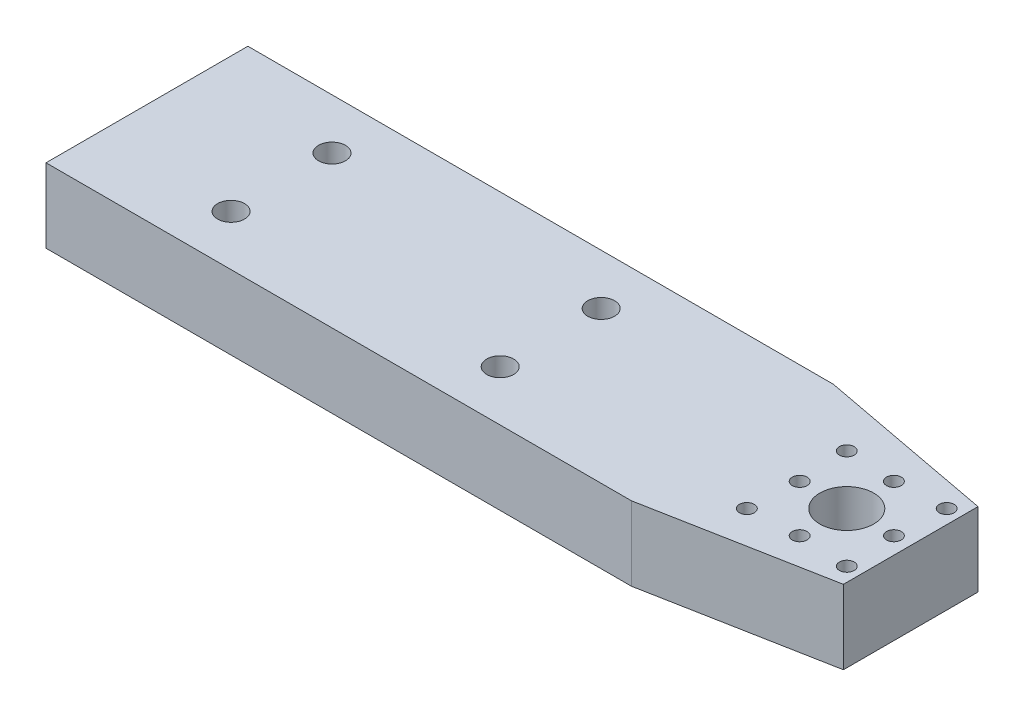
SolidWorks part; units mm, degrees
material "PF"
ref_plane "前视基准面" through (0, 0, 0) normal (0, 0, 1) x (1, 0, 0)
ref_plane "上视基准面" through (0, 0, 0) normal (0, 1, 0) x (1, 0, 0)
ref_plane "右视基准面" through (0, 0, 0) normal (1, 0, 0) x (0, 0, -1)
sketch "草图1" plane through (0, 0, 0) normal (0, 1, 0) x (1, 0, 0)
  line L1 (-41.2, 20) -> (78.8, 20)
  line L3 (-41.2, 0) -> (78.8, 0)
  line L4 (78.8, 20) -> (78.8, 0)
  arc A0 (-41.2, 20) -> (-41.2, 0) centre (-41.2, 10) ccw
  dimension "D1" = 20
  dimension "D2" = 120
extrude "凸台-拉伸1" add sketch "草图1" along normal blind 11
sketch "草图2" plane through (0, 11, 0) normal (0, 1, 0) x (1, 0, 0)
  line L0 (-41.2, 20) -> (-41.2, 0) construction
  line L1 (-41.2, 17) -> (-41.2, 3)
  circle A0 centre (-41.2, 3) radius 1.5
  circle A1 centre (-48.2, 10) radius 1.5
  circle A2 centre (-41.2, 17) radius 1.5
  circle A3 centre (-34.2, 10) radius 1.5
  circle A4 centre (-41.2, 10) radius 4
  point P7 (-41.2, 10)
  dimension "D1" = 4
extrude "切除-拉伸1" cut sketch "草图2" against normal blind 10 contours A1 | A2 L0 L1 | L0 A2 L1 | L1 L0 A0 | L0 L1 A0 | A4
sketch "草图4" plane through (0, 11, 0) normal (0, 1, 0) x (1, 0, 0)
  line L0 (78.8, 10) -> (69.3, 10) construction
  line L1 (78.8, 0) -> (78.8, 20) construction
  line L2 (78.8, 20) -> (78.8, 0)
  line L3 (69.3, 10) -> (76.7246, 17.4246)
  line L4 (69.3, 10) -> (62.3, 10)
  line L5 (69.3, 17) -> (69.3, 3) construction
  line L6 (69.3, 3) -> (69.3, 10) construction
  line L7 (61.8754, 17.4246) -> (69.3, 10) construction
  line L8 (69.3, 10) -> (76.7246, 2.5754) construction
  line L9 (76.7246, 2.5754) -> (69.3, 10) construction
  line L10 (61.8754, 2.5754) -> (69.3, 10) construction
  line L11 (61.8754, 2.5754) -> (69.3, 10) construction
  line L12 (69.3, 10) -> (52.3, 10) construction
  line L13 (52.3, 20) -> (52.3, 0)
  line L14 (-41.2, 0) -> (78.8, 0) construction
  line L15 (52.3, 12) -> (52.3, 16)
  line L16 (52.3, 12) -> (49.3, 12)
  line L17 (52.3, 16) -> (49.3, 16)
  line L18 (49.3, 12) -> (49.3, 16)
  line L20 (52.3, 4) -> (49.3, 4)
  line L21 (49.3, 8) -> (49.3, 4)
  line L22 (52.3, 8) -> (49.3, 8)
  line L23 (52.3, 8) -> (52.3, 4)
  circle A0 centre (76.7246, 17.4246) radius 1.1
  circle A1 centre (76.7246, 2.5754) radius 1.1
  circle A2 centre (61.8754, 2.5754) radius 1.1
  circle A3 centre (61.8754, 17.4246) radius 1.1
  circle A4 centre (62.3, 10) radius 1.1
  circle A5 centre (69.3, 17) radius 1.1
  circle A6 centre (76.3, 10) radius 1.1
  circle A7 centre (69.3, 3) radius 1.1
  circle A8 centre (69.3, 10) radius 4
  point P29 (52.3, 10)
  dimension "D2" = 4
  dimension "D3" = 4
  dimension "D8" = 8
  dimension "D1" = 9.5
  dimension "D4" = 7
  dimension "D5" = 17
  dimension "D6" = 3
  dimension "D7" = 4
extrude "切除-拉伸4" cut sketch "草图4" against normal blind 20
sketch "草图5" plane through (0, 0, 0) normal (0, -1, 0) x (1, 0, 0)
  line L0 (69.3, -10) -> (-34.7, -10) construction
  line L1 (-34.7, 0) -> (-34.7, -20)
  line L2 (-34.7, 0) -> (-53.3642, 0)
  line L3 (-34.7, -20) -> (-53.3642, -20)
  line L4 (-53.3642, 0) -> (-53.3642, -20)
  line L5 (-41.2, 0) -> (78.8, 0) construction
  line L6 (78.8, -20) -> (-41.2, -20) construction
  dimension "D1" = 104
extrude "切除-拉伸5" cut sketch "草图5" against normal blind 20
sketch "草图6" plane through (0, 11, 0) normal (0, 1, 0) x (1, 0, 0)
  line L0 (-34.7, 25) -> (-34.7, -5)
  line L1 (-34.7, 0) -> (-34.7, 20) construction
  line L2 (52.3, 25) -> (52.3, -5)
  line L3 (-34.7, 10) -> (52.3, 10) construction
  line L4 (78.8, 0) -> (78.8, 20) construction
  line L5 (52.3, 25) -> (-34.7, 25)
  line L6 (-34.7, -5) -> (52.3, -5)
  line L7 (52.3, -5) -> (78.8, 0)
  line L8 (78.8, 0) -> (52.3, 0)
  line L9 (-34.7, 0) -> (78.8, 0) construction
  line L10 (52.3, 0) -> (52.3, 20)
  line L11 (78.8, 20) -> (-34.7, 20) construction
  line L12 (52.3, 20) -> (78.8, 20)
  line L13 (78.8, 20) -> (52.3, 25)
  point P3 (-34.7, 10)
  point P7 (52.3, 10)
  line M7 (-34.7, 0) -> (78.8, 0)
  line M9 (78.8, 20) -> (-34.7, 20)
  dimension "D1" = 26.5
extrude "凸台-拉伸2" add sketch "草图6" against normal blind 11 contours L13 L2 M9 | L2 L7 M7 | L2 L5 L0 M9 | L0 L6 L2 M7
sketch "草图7" plane through (0, 11, 0) normal (0, 1, 0) x (1, 0, 0)
  line L0 (25.3, 17.5) -> (25.3, 2.5)
  line L1 (25.3, 17.5) -> (-14.7, 17.5)
  line L2 (25.3, 2.5) -> (-14.7, 2.5)
  line L3 (-14.7, 17.5) -> (-14.7, 2.5)
  line L5 (-34.7, 25) -> (-34.7, -5)
  line L6 (-34.7, 25) -> (-34.7, -5)
  circle A0 centre (25.3, 17.5) radius 2
  circle A1 centre (25.3, 2.5) radius 2
  circle A2 centre (-14.7, 17.5) radius 2
  circle A3 centre (-14.7, 2.5) radius 2
  point P0 (25.3, 10)
  point P3 (-14.7, 10)
  point P8 (-34.7, 10)
  dimension "D4" = 4
  dimension "D1" = 40
  dimension "D2" = 20
  dimension "D3" = 15
extrude "切除-拉伸6" cut sketch "草图7" against normal blind 11 contours L0 A0 L1 | L1 A0 L0 | L2 A1 L0 | L0 A1 L2 | L1 A2 L3 | L3 A2 L1 | L3 A3 L2
